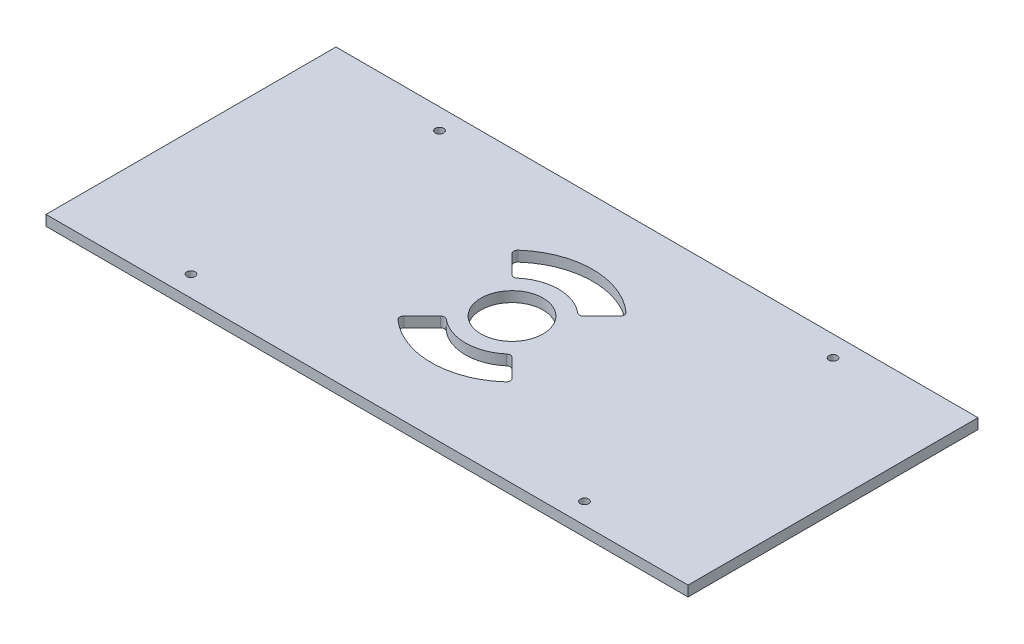
SolidWorks part; units mm, degrees
ref_plane "前视基准面" through (0, 0, 0) normal (0, 0, 1) x (1, 0, 0)
ref_plane "上视基准面" through (0, 0, 0) normal (0, 1, 0) x (1, 0, 0)
ref_plane "右视基准面" through (0, 0, 0) normal (1, 0, 0) x (0, 0, -1)
sketch "Sketch2" plane through (0, 0, 0) normal (0, 1, 0) x (1, 0, 0)
  line L1 (-155, 70) -> (155, 70)
  line L2 (-155, 70) -> (-155, -70)
  line L3 (-155, -70) -> (155, -70)
  line L4 (155, 70) -> (155, -70)
  line L5 (-155, 70) -> (155, -70) construction
  line L6 (-155, -70) -> (155, 70) construction
  point P0 (0, 0)
  dimension "D1" = 310
  dimension "D2" = 140
extrude "Boss-Extrude1" add sketch "Sketch2" along normal blind 5
sketch "Sketch3" plane through (0, 5, 0) normal (0, 1, 0) x (1, 0, 0)
  line L0 (155, -70) -> (155, 70) construction
  line L2 (155, 70) -> (-155, 70) construction
  circle A0 centre (0, 0) radius 15
  dimension "D1" = 30
  dimension "D3" = 70
  dimension "D2" = 155
extrude "Cut-Extrude1" cut sketch "Sketch3" against normal through all
sketch "Sketch5" plane through (0, 5, 0) normal (0, 1, 0) x (1, 0, 0)
  line L0 (-155, 0) -> (155, 0) construction
  line L1 (-155, 70) -> (-155, -70) construction
  line L2 (155, -70) -> (155, 70) construction
  line L3 (-155, 60) -> (155, 60) construction
  line L4 (155, 70) -> (-155, 70) construction
  line L5 (0, 0) -> (0, 70) construction
  circle A0 centre (-95, 60) radius 2
  circle A1 centre (95, 60) radius 2
  circle A2 centre (95, -60) radius 2
  circle A3 centre (-95, -60) radius 2
  dimension "D2" = 60
  dimension "D3" = 4
  dimension "D1" = 10
extrude "Cut-Extrude2" cut sketch "Sketch5" against normal through all
sketch "Sketch6" plane through (0, 5, 0) normal (0, 1, 0) x (1, 0, 0)
  line L0 (0, 0) -> (27.5772, 27.5772)
  line L1 (0, 0) -> (39, 0) construction
  line L2 (0, 0) -> (27.5772, -27.5772)
  line L3 (0, 0) -> (-27.5772, -27.5772)
  line L4 (0, 0) -> (-27.5772, 27.5772)
  circle A0 centre (0, 0) radius 39
  circle A1 centre (0, 0) radius 22.5
  point P12 (0, 0)
  dimension "D1" = 78
  dimension "D2" = 45
  dimension "D3" = 45
  dimension "D4" = 4
extrude "Cut-Extrude3" cut sketch "Sketch6" against normal blind 10 contours A1 L3 A0 L2 | A1 L0 A0 L4
fillet "Fillet1" radius 2 8 edges at (15.9099, 2.5, 15.9099) (27.5772, 2.5, 27.5772) (-27.5772, 2.5, 27.5772) (-15.9099, 2.5, 15.9099) (-15.9099, 2.5, -15.9099) (27.5772, 2.5, -27.5772) (15.9099, 2.5, -15.9099) (-27.5772, 2.5, -27.5772)
